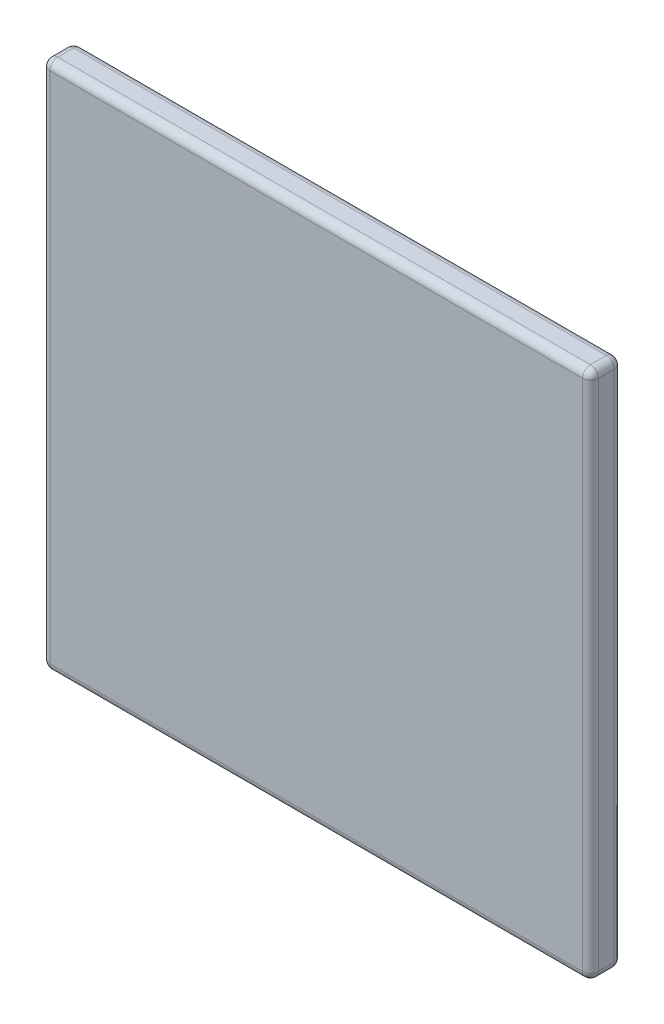
SolidWorks part; units mm, degrees
ref_plane "Front Plane" through (0, 0, 0) normal (0, 0, 1) x (1, 0, 0)
ref_plane "Top Plane" through (0, 0, 0) normal (0, 1, 0) x (1, 0, 0)
ref_plane "Right Plane" through (0, 0, 0) normal (1, 0, 0) x (0, 0, -1)
sketch "Sketch1" plane through (0, 0, 0) normal (0, 0, 1) x (1, 0, 0)
  line L1 (-17.35, -16.75) -> (17.35, -16.75)
  line L2 (-17.35, -16.75) -> (-17.35, 16.75)
  line L3 (-17.35, 16.75) -> (17.35, 16.75)
  line L4 (17.35, -16.75) -> (17.35, 16.75)
  line L5 (-17.35, -16.75) -> (17.35, 16.75) construction
  line L6 (-17.35, 16.75) -> (17.35, -16.75) construction
  point P0 (0, 0)
  dimension "D1" = 34.7
  dimension "D2" = 33.5
extrude "Boss-Extrude1" add sketch "Sketch1" along normal blind 2
fillet "Fillet1" radius 0.5 12 edges at (0, -16.75, 2) (0, -16.75, 0) (-17.35, 0, 2) (-17.35, -16.75, 1) (-17.35, 0, 0) (0, 16.75, 2) (-17.35, 16.75, 1) (0, 16.75, 0) (17.35, -16.75, 1) (17.35, 0, 2) (17.35, 16.75, 1) (17.35, 0, 0)
